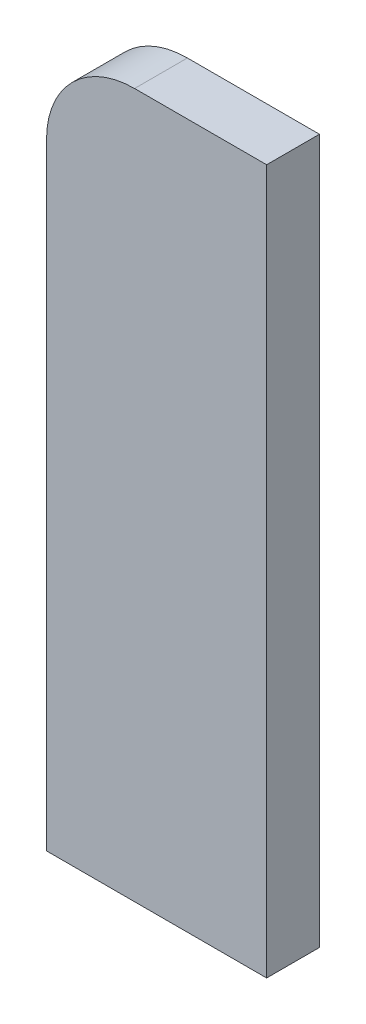
SolidWorks part; units mm, degrees
ref_plane "Plan de face" through (0, 0, 0) normal (0, 0, 1) x (1, 0, 0)
ref_plane "Plan de dessus" through (0, 0, 0) normal (0, 1, 0) x (1, 0, 0)
ref_plane "Plan de droite" through (0, 0, 0) normal (1, 0, 0) x (0, 0, -1)
sketch "Esquisse1" plane through (0, 0, 0) normal (0, 0, 1) x (1, 0, 0)
  line L1 (-30, 50) -> (-5, 50)
  line L2 (-30, 50) -> (-30, -30)
  line L3 (-30, -30) -> (-5, -30)
  line L4 (-5, 50) -> (-5, -30)
  dimension "D1" = 80
  dimension "D2" = 25
extrude "Extrusion1" add sketch "Esquisse1" along normal blind 6
fillet "Congé1" radius 10 1 edges at (-30, 50, 3)
